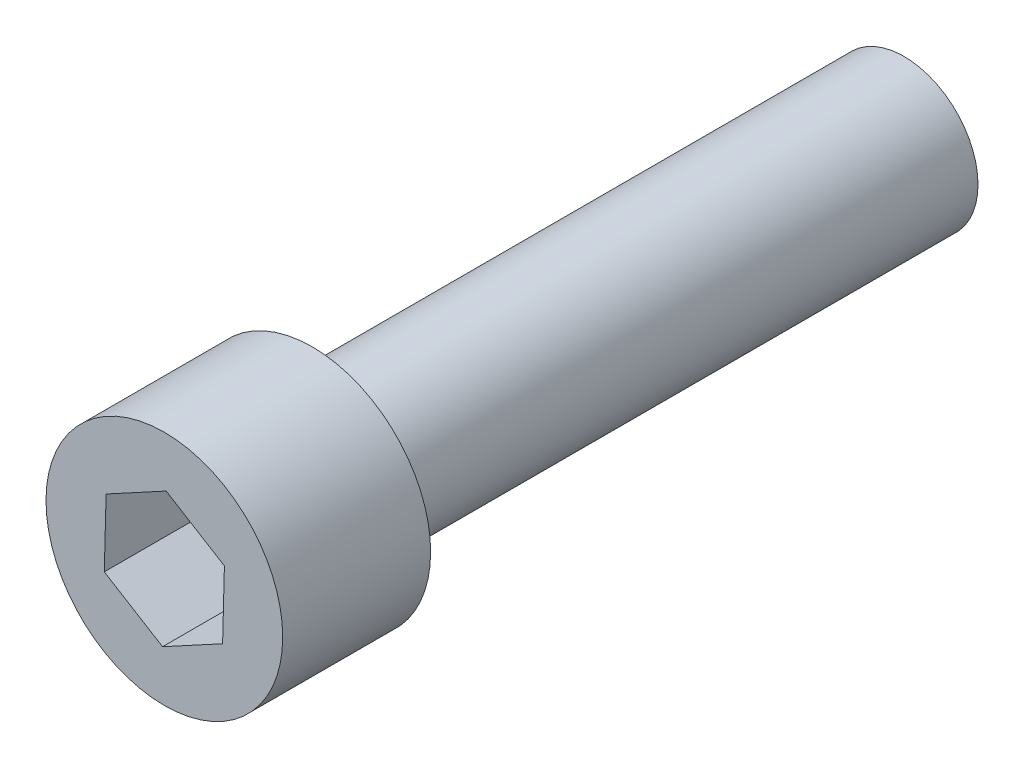
SolidWorks part; units mm, degrees
ref_plane "前视基准面" through (0, 0, 0) normal (0, 0, 1) x (1, 0, 0)
ref_plane "上视基准面" through (0, 0, 0) normal (0, 1, 0) x (1, 0, 0)
ref_plane "右视基准面" through (0, 0, 0) normal (1, 0, 0) x (0, 0, -1)
sketch "草图1" plane through (0, 0, 0) normal (0, 0, 1) x (1, 0, 0)
  circle A0 centre (0, 0) radius 2.5
  dimension "D1" = 5
extrude "凸台-拉伸1" add sketch "草图1" along normal blind 20
sketch "草图2" plane through (0, 0, 20) normal (0, 0, 1) x (1, 0, 0)
  circle A0 centre (0, 0) radius 4
  dimension "D1" = 8
extrude "凸台-拉伸2" add sketch "草图2" along normal blind 5
sketch "草图3" plane through (0, 0, 25) normal (0, 0, 1) x (1, 0, 0)
  line L1 (1.9689, -1.2069) -> (2.0297, 1.1017)
  line L2 (2.0297, 1.1017) -> (0.0608, 2.3086)
  line L3 (0.0608, 2.3086) -> (-1.9689, 1.2069)
  line L4 (-1.9689, 1.2069) -> (-2.0297, -1.1017)
  line L5 (-2.0297, -1.1017) -> (-0.0608, -2.3086)
  line L6 (-0.0608, -2.3086) -> (1.9689, -1.2069)
  circle A0 centre (0, 0) radius 2 construction
  point P1 (-1.9993, 0.0526)
  dimension "D1" = 4
extrude "切除-拉伸1" cut sketch "草图3" against normal blind 5
